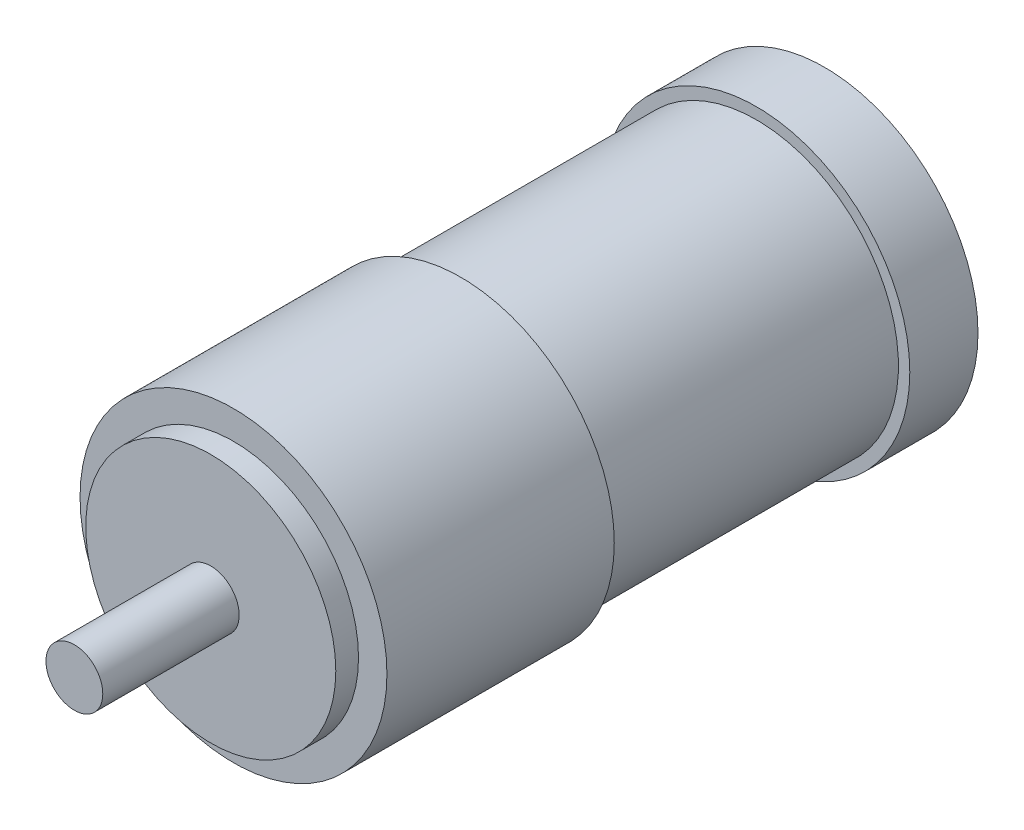
SolidWorks part; units mm, degrees
ref_plane "Front Plane" through (0, 0, 0) normal (0, 0, 1) x (1, 0, 0)
ref_plane "Top Plane" through (0, 0, 0) normal (0, 1, 0) x (1, 0, 0)
ref_plane "Right Plane" through (0, 0, 0) normal (1, 0, 0) x (0, 0, -1)
sketch "Sketch1" plane through (0, 0, 0) normal (0, 0, 1) x (1, 0, 0)
  circle A0 centre (0, 0) radius 12.5
  dimension "D1" = 25
extrude "Boss-Extrude1" add sketch "Sketch1" along normal blind 52
sketch "Sketch2" plane through (0, 0, 52) normal (0, 0, 1) x (1, 0, 0)
  circle A0 centre (0, 0) radius 11
  dimension "D1" = 22
extrude "Boss-Extrude3" add sketch "Sketch2" along normal blind 2
sketch "Sketch4" plane through (0, 0, 54) normal (0, 0, 1) x (1, 0, 0)
  circle A0 centre (0, 0) radius 2.5
  dimension "D1" = 5
extrude "Boss-Extrude4" add sketch "Sketch4" along normal blind 12
sketch "Sketch5" plane through (0, 0, 52) normal (0, 0, 1) x (1, 0, 0)
  circle A1 centre (0, 0) radius 12.5 construction
  circle A2 centre (0, 0) radius 13.5
  circle A3 centre (0, 0) radius 13.5
  circle A4 centre (0, 0) radius 12.5
  dimension "D1" = 1
extrude "Boss-Extrude5" add sketch "Sketch5" along normal blind 20 from offset 20 offset against normal yes
sketch "Sketch6" plane through (0, 0, 0) normal (0, 0, -1) x (-1, 0, 0)
  circle A2 centre (0, 0) radius 13.5
  circle A3 centre (0, 0) radius 13.5
  dimension "D1" = 1
extrude "Boss-Extrude6" add sketch "Sketch6" against normal blind 6
sketch "Sketch8" plane through (0, 0, 0) normal (0, 0, -1) x (-1, 0, 0)
  circle A0 centre (0, 0) radius 9
  dimension "D1" = 18
extrude "Boss-Extrude7" add sketch "Sketch8" along normal blind 2
sketch "Sketch9" plane through (0, 0, 0) normal (0, 0, -1) x (-1, 0, 0)
  circle A2 centre (0, 0) radius 12.5
  circle A3 centre (0, 0) radius 12.5
  dimension "D1" = 1
extrude "Cut-Extrude3" cut sketch "Sketch9" against normal blind 2 contours A3
